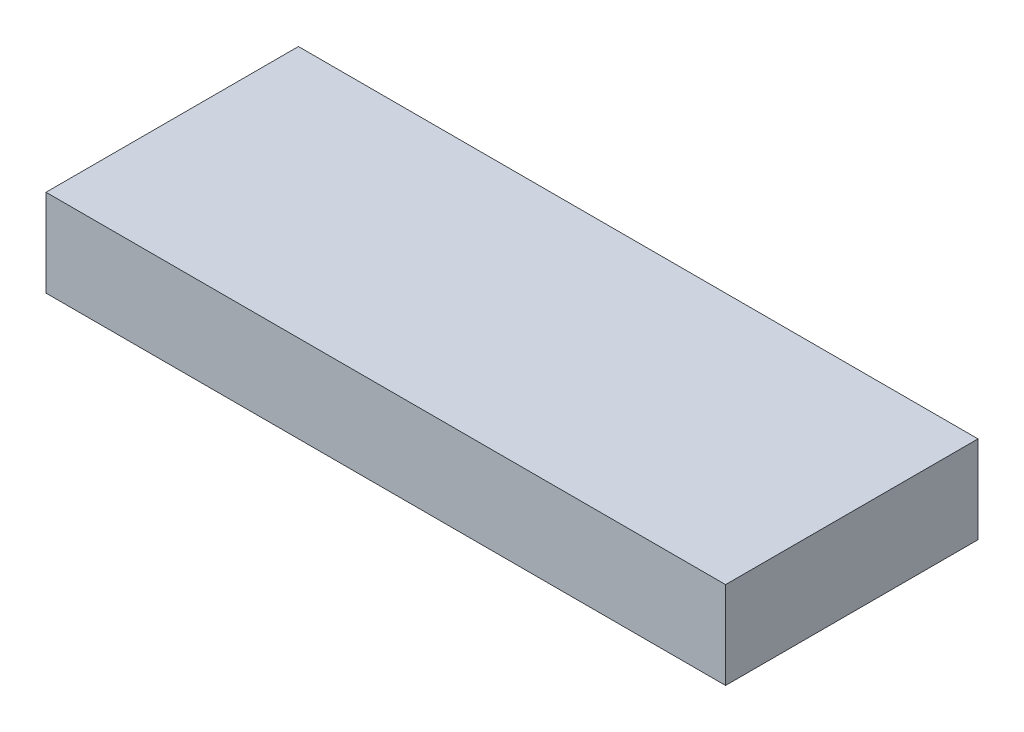
SolidWorks part; units mm, degrees
ref_plane "Front Plane" through (0, 0, 0) normal (0, 0, 1) x (1, 0, 0)
ref_plane "Top Plane" through (0, 0, 0) normal (0, 1, 0) x (1, 0, 0)
ref_plane "Right Plane" through (0, 0, 0) normal (1, 0, 0) x (0, 0, -1)
sketch "Sketch1" plane through (0, 0, 0) normal (0, 1, 0) x (1, 0, 0)
  line L1 (-70, 26) -> (70, 26)
  line L2 (-70, 26) -> (-70, -26)
  line L3 (-70, -26) -> (70, -26)
  line L4 (70, 26) -> (70, -26)
  line L5 (-70, 26) -> (70, -26) construction
  line L6 (-70, -26) -> (70, 26) construction
  point P0 (0, 0)
  dimension "D1" = 52
  dimension "D2" = 140
extrude "Boss-Extrude1" add sketch "Sketch1" along normal mid plane 18
